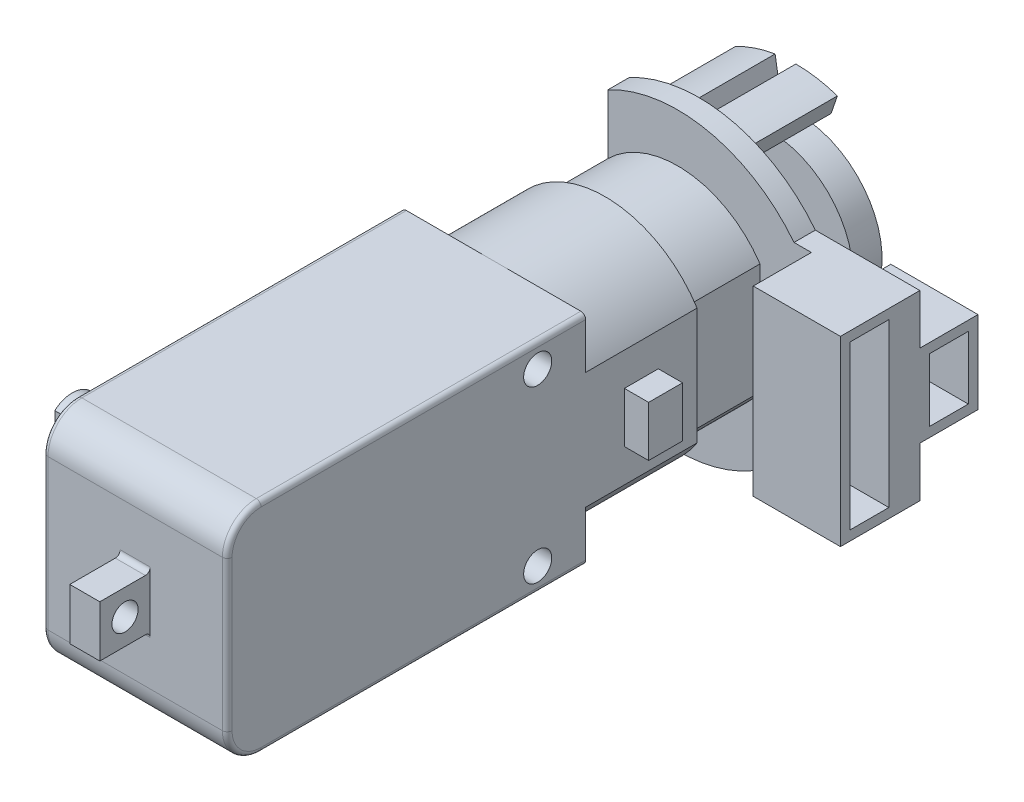
SolidWorks part; units mm, degrees
ref_plane "Front Plane" through (0, 0, 0) normal (0, 0, 1) x (1, 0, 0)
ref_plane "Top Plane" through (0, 0, 0) normal (0, 1, 0) x (1, 0, 0)
ref_plane "Right Plane" through (0, 0, 0) normal (1, 0, 0) x (0, 0, -1)
sketch "Sketch1" plane through (0, 0, 0) normal (1, 0, 0) x (0, 0, -1)
  line L0 (0, 0) -> (-38.2014, 0) construction
  line L2 (-37, -11.25) -> (0, -11.25)
  line L3 (-37, -11.25) -> (-37, 11.25)
  line L4 (-37, 11.25) -> (0, 11.25)
  line L5 (0, -11.25) -> (0, 11.25)
  line L6 (-37, -11.25) -> (0, 11.25) construction
  line L7 (-37, 11.25) -> (0, -11.25) construction
  point P3 (-18.5, 0)
  dimension "D1" = 22.5
  dimension "D2" = 37
extrude "Boss-Extrude1" add sketch "Sketch1" along normal blind 19
sketch "Sketch2" plane through (0, 0, 37) normal (0, 0, 1) x (1, 0, 0)
  line L0 (9.5, 11.25) -> (9.5, -11.25) construction
  line L1 (19, 11.25) -> (0, 11.25) construction
  line L2 (19, -11.25) -> (0, -11.25) construction
  line L3 (0, 0) -> (19, 0) construction
  line L4 (19, 11.25) -> (19, -11.25) construction
  line L6 (7.95, -2.65) -> (11.05, -2.65)
  line L7 (7.95, -2.65) -> (7.95, 2.65)
  line L8 (7.95, 2.65) -> (11.05, 2.65)
  line L9 (11.05, -2.65) -> (11.05, 2.65)
  line L10 (7.95, -2.65) -> (11.05, 2.65) construction
  line L11 (7.95, 2.65) -> (11.05, -2.65) construction
  point P11 (9.5, 0)
  dimension "D1" = 3.1
  dimension "D2" = 5.3
extrude "Boss-Extrude2" add sketch "Sketch2" along normal blind 5.2
sketch "Sketch3" plane through (11.05, 0, 0) normal (1, 0, 0) x (0, 0, -1)
  line L0 (-42.2, 2.65) -> (-37, -2.65) construction
  line L1 (-42.2, -2.65) -> (-37, 2.65) construction
  line L2 (-37, 11.25) -> (-37, -11.25) construction
  line L3 (-37, -2.65) -> (-37, 2.65) construction
  line L4 (-42.2, 2.65) -> (-37, 2.65) construction
  circle A0 centre (-39.6, 0) radius 1.35
  dimension "D1" = 2.7
extrude "Cut-Extrude1" cut sketch "Sketch3" against normal through all
fillet "Fillet1" radius 3.5 2 edges at (9.5, -11.25, 37) (9.5, 11.25, 37)
sketch "Sketch4" plane through (19, 0, 0) normal (1, 0, 0) x (0, 0, -1)
  line L0 (-25, 11.25) -> (-25, -11.25) construction
  line L1 (0, 11.25) -> (-33.5, 11.25) construction
  line L2 (-33.5, -11.25) -> (0, -11.25) construction
  line L3 (-37, 0) -> (0, 0) construction
  line L4 (-37, 7.75) -> (-37, -7.75) construction
  circle A0 centre (-25, 0) radius 3.6
  dimension "D2" = 7.2
  dimension "D1" = 12
extrude "Boss-Extrude3" add sketch "Sketch4" along normal blind 0.1
sketch "Sketch5" plane through (0, 0, 0) normal (-1, 0, 0) x (0, 0, 1)
  circle A0 centre (25, 0) radius 3.6 construction
  circle A1 centre (25, 0) radius 3.6
extrude "Boss-Extrude4" add sketch "Sketch5" along normal blind 0.1
sketch "Sketch6" plane through (19.1, 0, 0) normal (1, 0, 0) x (0, 0, -1)
  circle A0 centre (-25, 0) radius 2.7
  dimension "D1" = 5.4
extrude "Boss-Extrude5" add sketch "Sketch6" along normal blind 8.9
sketch "Sketch7" plane through (-0.1, 0, 0) normal (-1, 0, 0) x (0, 0, 1)
  circle A0 centre (25, 0) radius 2.7 construction
  circle A1 centre (25, 0) radius 2.7
extrude "Boss-Extrude6" add sketch "Sketch7" along normal blind 8.9
fillet "Fillet2" radius 0.5 2 edges at (9.5, -2.65, 37) (9.5, 2.65, 37)
sketch "Sketch8" plane through (28, 0, 0) normal (1, 0, 0) x (0, 0, -1)
  line L0 (-26.8, 2.0125) -> (-26.8, -2.0125)
  line L2 (-23.2, -2.0125) -> (-23.2, 2.0125)
  circle A0 centre (-25, 0) radius 2.7 construction
  circle A1 centre (-25, 0) radius 2.7
  circle M3 centre (-25, 0) radius 2.7
  dimension "D1" = 3.6
extrude "Cut-Extrude2" cut sketch "Sketch8" against normal blind 8.2 contours L0 M3 | L2 M3
sketch "Sketch9" plane through (-9, 0, 0) normal (-1, 0, 0) x (0, 0, 1)
  line L0 (26.8, 2.0125) -> (26.8, -2.0125) construction
  line L1 (23.2, -2.0125) -> (23.2, 2.0125) construction
  line L2 (26.8, 2.0125) -> (26.8, -2.0125)
  line L3 (23.2, -2.0125) -> (23.2, 2.0125)
  circle A0 centre (25, 0) radius 2.7 construction
  circle A1 centre (25, 0) radius 2.7
  circle M1 centre (25, 0) radius 2.7
extrude "Cut-Extrude3" cut sketch "Sketch9" against normal blind 8.2 contours L3 M1 | L2 M1
hole_wizard "M2x0.4 Tapped Hole1" positions "Sketch11" profile "Sketch10" tap size "M2x0.4" standard "ANSI Metric"
sketch "Sketch11" plane through (28, 0, 0) normal (1, 0, 0) x (0, 0, -1)
  point P0 (-25, 0)
sketch "Sketch10" plane through (28, 0, 25) normal (0, 1, 0) x (0, 0, -1)
  line L0 (0, 0) -> (0, 5.6807)
  line L1 (0, 5.6807) -> (0.8, 5.2)
  line L2 (0.8, 5.2) -> (0.8, 0)
  line L5 (0.8, 0) -> (0, 0)
  line L10 (0, 5.6807) -> (-0.8, 5.2) construction
  line L11 (0, -6.35) -> (0, 107.95) construction
  dimension "Tap Drill Dia." = 1.6
  dimension "Tap Drill Depth" = 5.2
  dimension "Drill Angle" = 118
cosmetic thread "Hole Thread1" parameters "D1"=4, "D2"=2
hole_wizard "M2x0.4 Tapped Hole2" positions "Sketch15" profile "Sketch14" tap size "M2x0.4" standard "ANSI Metric"
sketch "Sketch15" plane through (-9, 0, 0) normal (-1, 0, 0) x (0, 0, 1)
  point P0 (25, 0)
sketch "Sketch14" plane through (-9, 0, 25) normal (0, 1, 0) x (0, 0, 1)
  line L0 (0, 0) -> (0, 5.6807)
  line L1 (0, 5.6807) -> (0.8, 5.2)
  line L2 (0.8, 5.2) -> (0.8, 0)
  line L5 (0.8, 0) -> (0, 0)
  line L10 (0, 5.6807) -> (-0.8, 5.2) construction
  line L11 (0, -6.35) -> (0, 107.95) construction
  dimension "Tap Drill Dia." = 1.6
  dimension "Tap Drill Depth" = 5.2
  dimension "Drill Angle" = 118
cosmetic thread "Hole Thread2" parameters "D1"=4, "D2"=2
sketch "Sketch16" plane through (0, 0, 0) normal (-1, 0, 0) x (0, 0, 1)
  line L0 (0, 0) -> (21.4, 0) construction
  circle A0 centre (25, 0) radius 3.6 construction
  circle A1 centre (13.75, 0) radius 1.95
  circle A4 centre (25, 0) radius 3.6 construction
  dimension "D1" = 3.9
  dimension "D2" = 5.7
extrude "Boss-Extrude7" add sketch "Sketch16" along normal blind 2
sketch "Sketch17" plane through (0, 0, 0) normal (0, 0, -1) x (-1, 0, 0)
  line L0 (-19, 11.25) -> (0, -11.25) construction
  line L1 (-19, -11.25) -> (0, 11.25) construction
  line L2 (-19, -11.25) -> (-19, 11.25) construction
  line L3 (-19, -11.25) -> (-19, 11.25)
  line L6 (-1.3, -11.25) -> (-1.3, 11.25)
  line L7 (-1.3, -11.25) -> (-1.3, 11.25)
  circle A0 centre (-9.5, 0) radius 11.25
  dimension "D1" = 1.3
extrude "Boss-Extrude8" add sketch "Sketch17" along normal blind 11.5 contours L7 A0 L3
sketch "Sketch18" plane through (19, 0, 0) normal (1, 0, 0) x (0, 0, -1)
  line L0 (11.5, 0) -> (0, 0) construction
  line L1 (11.5, 6.026) -> (11.5, -6.026) construction
  line L3 (4, -2.6) -> (7.5, -2.6)
  line L4 (4, -2.6) -> (4, 2.6)
  line L5 (4, 2.6) -> (7.5, 2.6)
  line L6 (7.5, -2.6) -> (7.5, 2.6)
  line L7 (4, -2.6) -> (7.5, 2.6) construction
  line L8 (4, 2.6) -> (7.5, -2.6) construction
  point P5 (5.75, 0)
  dimension "D1" = 4
  dimension "D2" = 5.2
  dimension "D3" = 3.5
extrude "Boss-Extrude9" add sketch "Sketch18" along normal blind 2.5
sketch "Sketch19" plane through (1.3, 0, 0) normal (-1, 0, 0) x (0, 0, 1)
  line L0 (-7.5, 2.6) -> (-4, 2.6) construction
  line L1 (-4, 2.6) -> (-4, -2.6) construction
  line L2 (-4, -2.6) -> (-7.5, -2.6) construction
  line L3 (-7.5, -2.6) -> (-7.5, 2.6) construction
  line L4 (-7.5, 2.6) -> (-4, 2.6)
  line L5 (-4, 2.6) -> (-4, -2.6)
  line L6 (-4, -2.6) -> (-7.5, -2.6)
  line L7 (-7.5, -2.6) -> (-7.5, 2.6)
extrude "Boss-Extrude10" add sketch "Sketch19" along normal blind 2.5
sketch "Sketch20" plane through (0, 0, -11.5) normal (0, 0, -1) x (-1, 0, 0)
  line L20 (-18, 6.026) -> (-18, -6.026)
  line L21 (-18, 5.7282) -> (-18, -5.7282)
  line L23 (-2.3, -7.7021) -> (-2.3, 7.7021)
  line L24 (-2.3, -7.2954) -> (-2.3, 7.2954)
  arc A30 (-2.0289, 7.0175) -> (-18.1556, 5.4903) centre (-9.5, 0) ccw
  arc A31 (-2.3, 7.2954) -> (-18, 5.7282) centre (-9.5, 0) ccw
  arc A34 (-18.1556, -5.4903) -> (-2.0289, -7.0175) centre (-9.5, 0) ccw
  arc A35 (-18, -5.7282) -> (-2.3, -7.2954) centre (-9.5, 0) ccw
  dimension "D1" = 1
  dimension "D2" = 1
  dimension "D3" = 1
  dimension "D4" = 1
extrude "Boss-Extrude11" add sketch "Sketch20" along normal blind 13.5
fillet "Fillet3" radius 1.7 2 edges at (10.5181, -10.1993, -25) (10.5181, 10.1993, -25)
sketch "Sketch21" plane through (0, 0, -25) normal (0, 0, -1) x (-1, 0, 0)
  line L0 (-5.5, 3) -> (-5.5, -3)
  circle A0 centre (-9.5, 0) radius 5
  dimension "D1" = 10
  dimension "D2" = 9
extrude "Boss-Extrude12" add sketch "Sketch21" along normal blind 2 contours L0 A0
sketch "Sketch23" plane through (0, 0, -25) normal (0, 0, -1) x (-1, 0, 0)
  line L0 (-9.5, 10.25) -> (-9.5, -11.25) construction
  line L1 (-7.9, 7) -> (-7.9, -7) construction
  line L2 (-11.1, 13.5) -> (-7.9, 13.5)
  line L3 (-11.1, 13.5) -> (-11.1, 7)
  line L4 (-11.1, 7) -> (-7.9, 7)
  line L5 (-7.9, 13.5) -> (-7.9, 7)
  line L6 (-11.1, 13.5) -> (-7.9, 7) construction
  line L7 (-11.1, 7) -> (-7.9, 13.5) construction
  line L8 (-11.1, -15.5) -> (-7.9, -15.5)
  line L9 (-11.1, -15.5) -> (-11.1, -7)
  line L10 (-11.1, -7) -> (-7.9, -7)
  line L11 (-7.9, -15.5) -> (-7.9, -7)
  line L12 (-11.1, -15.5) -> (-7.9, -7) construction
  line L13 (-11.1, -7) -> (-7.9, -15.5) construction
  line L14 (-9.5, 0) -> (-7.9, 7) construction
  line L16 (-9.5, 0) -> (-7.9, -7) construction
  arc A0 (-2.3, 7.2954) -> (-18, 5.7282) centre (-9.5, 0) ccw construction
  arc A1 (-2.3, 4.6111) -> (-18, 0.9233) centre (-9.5, 0) ccw construction
  arc A2 (-2.3, 4.6111) -> (-18, 0.9233) centre (-9.5, 0) ccw construction
  dimension "D1" = 14
  dimension "D2" = 3.2
extrude "Cut-Extrude4" cut sketch "Sketch23" against normal blind 6
sketch "Sketch24" plane through (0, -11.25, 0) normal (0, -1, 0) x (1, 0, 0)
  line L0 (19, 25) -> (0, 25) construction
  line L1 (19, 33.5) -> (19, 0) construction
  line L2 (0, 33.5) -> (0, 0) construction
  line L3 (28, 25) -> (19, 25) construction
  line L4 (28, 23.2) -> (28, 26.8) construction
ref_plane "Plane1" through (0, 0, 25) normal (0, 0, 1) x (-1, 0, 0)
sketch "Sketch25" plane through (19, 0, 0) normal (1, 0, 0) x (0, 0, -1)
  line L0 (-4.95, 11.25) -> (-4.95, -11.25) construction
  line L1 (0, 11.25) -> (-33.5, 11.25) construction
  line L2 (-33.5, -11.25) -> (0, -11.25) construction
  line L4 (0, 6.026) -> (0, 11.25) construction
  line L5 (-37, 7.75) -> (-37, -7.75) construction
  circle A0 centre (-4.95, 8.8) radius 1.45
  circle A1 centre (-4.95, -8.8) radius 1.45
  dimension "D1" = 2.9
  dimension "D2" = 14.7
  dimension "D5" = 3.5
  dimension "D3" = 1
  dimension "D4" = 1
  dimension "D6" = 30.6
extrude "Cut-Extrude5" cut sketch "Sketch25" against normal through all
fillet "Fillet4" radius 0.5 10 edges at (0, -11.25, 16.75) (0, -10.2249, 35.9749) (0, 0, 37) (0, 10.2249, 35.9749) (19, -11.25, 16.75) (19, -10.2249, 35.9749) (19, 0, 37) (19, 10.2249, 35.9749) (0, 11.25, 16.75) (19, 11.25, 16.75)
sketch "Sketch26" plane through (0, 0, -27) normal (0, 0, -1) x (-1, 0, 0)
  circle A0 centre (-9.5, 0) radius 1
  dimension "D1" = 2
extrude "Boss-Extrude13" add sketch "Sketch26" along normal blind 4.5
sketch "Sketch27" plane through (0, 0, 0) normal (-1, 0, 0) x (0, 0, 1)
  line L0 (25, 0) -> (16.1055, -5.3723) construction
sketch "Sketch28" plane through (0, 0, -31.5) normal (0, 0, -1) x (-1, 0, 0)
  circle A0 centre (-9.5, 0) radius 8.6
  dimension "D1" = 17.2
extrude "Boss-Extrude14" add sketch "Sketch28" against normal blind 3
sketch "Sketch29" plane through (0, 0, -19) normal (0, 0, -1) x (-1, 0, 0)
  line L0 (-18, 5.7282) -> (-18, -5.7282) construction
  line L1 (-18, 5.7282) -> (-18, -5.7282)
  line L2 (-2.3, 7.2954) -> (-2.3, 13.4433)
  line L3 (-9.5, 0) -> (-39.9184, 0) construction
  line L4 (-23, 7.0931) -> (-23, -7.0931)
  line L5 (-2.3, 7.2954) -> (10.3813, 16.3683) construction
  line L6 (-2.3, -7.2954) -> (-2.3, -13.4433)
  line L7 (-7.9, -8.399) -> (-7.9, -10.1244) construction
  line L8 (-2.3, 13.4433) -> (7.472, 20.4347) construction
  line L9 (-32.3, -9.4) -> (-21.5084, -9.4)
  line L10 (-32.3, -9.4) -> (-32.3, 9.4)
  line L11 (-32.3, 9.4) -> (-21.5084, 9.4)
  line L12 (-21.5084, -9.4) -> (-21.5084, 9.4)
  line L13 (-32.3, -9.4) -> (-21.5084, 9.4) construction
  line L14 (-32.3, 9.4) -> (-21.5084, -9.4) construction
  line L15 (-11.1, -10.1244) -> (-11.1, -8.399) construction
  line L16 (-7.9, -8.399) -> (-7.9, -10.1244)
  line L17 (-11.1, -10.1244) -> (-11.1, -8.399)
  line L18 (-7.9, 10.1244) -> (-7.9, 8.399) construction
  line L19 (-11.1, 8.399) -> (-11.1, 10.1244) construction
  line L20 (-7.9, 10.1244) -> (-7.9, 8.399)
  line L21 (-11.1, 8.399) -> (-11.1, 10.1244)
  arc A0 (-2.3, 7.2954) -> (-18, 5.7282) centre (-9.5, 0) ccw construction
  arc A1 (-2.3, 7.2954) -> (-7.9, 10.1244) centre (-9.5, 0) ccw
  arc A2 (-18, -5.7282) -> (-2.3, -7.2954) centre (-9.5, 0) ccw construction
  arc A3 (-18, -5.7282) -> (-11.1, -10.1244) centre (-9.5, 0) ccw
  arc A4 (-2.3, 13.4433) -> (-23, 7.0931) centre (-9.5, 0) ccw
  arc A5 (-23, -7.0931) -> (-2.3, -13.4433) centre (-9.5, 0) ccw
  arc A6 (-23, -7.0931) -> (1.2122, -10.8541) centre (-9.5, 0) ccw construction
  arc A9 (-7.9, -10.1244) -> (-2.3, -7.2954) centre (-9.5, 0) ccw
  arc A10 (-18, -5.7282) -> (-2.3, -7.2954) centre (-9.5, 0) ccw construction
  arc A11 (-11.1, 10.1244) -> (-18, 5.7282) centre (-9.5, 0) ccw
  arc A12 (-2.3, 7.2954) -> (-18, 5.7282) centre (-9.5, 0) ccw construction
  arc A13 (-11.1, -10.1244) -> (-7.9, -10.1244) centre (-9.5, 0) ccw construction
  arc A14 (-11.1, -10.1244) -> (-7.9, -10.1244) centre (-9.5, 0) ccw
  arc A15 (-7.9, 10.1244) -> (-11.1, 10.1244) centre (-9.5, 0) ccw construction
  arc A16 (-7.9, 10.1244) -> (-11.1, 10.1244) centre (-9.5, 0) ccw
  arc A17 (-11.1, 9.2617) -> (-7.9, 9.2617) centre (-9.5, 11.7994) ccw
  arc A18 (-11.1, -9.2617) -> (-7.9, -9.2617) centre (-9.5, -11.7994) cw
  point P21 (-26.9042, 0)
  arc M18 (-7.9, 10.1244) -> (-11.1, 10.1244) centre (-9.5, 0) ccw
  line M19 (-11.1, 10.1244) -> (-11.1, 7)
  dimension "D1" = 3
  dimension "D5" = 3
  dimension "D3" = 18.8
  dimension "D4" = 30
  dimension "D2" = 5
extrude "Boss-Extrude20" add sketch "Sketch29" along normal blind 2.2 contours A14 A3 L1 A11 A1 L2 A4 L12 A5 L6 A9 M18 | A18 L17 A14 L16 | A17 L20 M19 M18 | A5 L4 A4 L11 L10 L9 | L4 A5 L12 A4
sketch "Sketch30" plane through (0, 0, -19) normal (0, 0, 1) x (1, 0, 0)
  line L0 (32.3, -9.4) -> (21.5084, -9.4) construction
  line L1 (32.3, 9.4) -> (23.3, 9.4)
  line L2 (32.3, 9.4) -> (32.3, -9.4)
  line L3 (32.3, -9.4) -> (23.3, -9.4)
  line L4 (23.3, 9.4) -> (23.3, -9.4)
  dimension "D1" = 9
extrude "Boss-Extrude21" add sketch "Sketch30" along normal blind 6
sketch "Sketch31" plane through (0, 0, -21.2) normal (0, 0, -1) x (-1, 0, 0)
  line L0 (-32.3, -9.4) -> (-32.3, 9.4) construction
  line L1 (-32.3, 4.25) -> (-23.3, 4.25)
  line L2 (-32.3, 4.25) -> (-32.3, -4.25)
  line L3 (-32.3, -4.25) -> (-23.3, -4.25)
  line L4 (-23.3, 4.25) -> (-23.3, -4.25)
  line L5 (-23.3, 0) -> (-9.5, 0) construction
  dimension "D1" = 9
  dimension "D2" = 8.5
extrude "Boss-Extrude22" add sketch "Sketch31" along normal blind 6
sketch "Sketch32" plane through (32.3, 0, 0) normal (1, 0, 0) x (0, 0, -1)
  line L8 (18, 8.4) -> (18, -8.4)
  line L9 (22.2, 3.25) -> (22.2, -3.25)
  line L10 (19, 15.25) -> (19, 9.4) construction
  line L11 (21.2, 5.7282) -> (21.2, 10.1244) construction
  line L16 (20.2, 8.4) -> (14, 8.4)
  line L17 (14, 8.4) -> (14, -8.4)
  line L18 (14, -8.4) -> (20.2, -8.4)
  line L19 (20.2, -8.4) -> (20.2, -3.25)
  line L20 (20.2, -3.25) -> (26.2, -3.25)
  line L21 (26.2, -3.25) -> (26.2, 3.25)
  line L22 (26.2, 3.25) -> (20.2, 3.25)
  line L23 (20.2, 3.25) -> (20.2, 8.4)
  line L24 (20.2, 8.4) -> (14, 8.4)
  line L25 (14, 8.4) -> (14, -8.4)
  line L26 (14, -8.4) -> (20.2, -8.4)
  line L27 (20.2, -8.4) -> (20.2, -3.25)
  line L28 (20.2, -3.25) -> (26.2, -3.25)
  line L29 (26.2, -3.25) -> (26.2, 3.25)
  line L30 (26.2, 3.25) -> (20.2, 3.25)
  line L31 (20.2, 3.25) -> (20.2, 8.4)
  dimension "D2" = 1
  dimension "D3" = 1
  dimension "D1" = 1
extrude "Cut-Extrude6" cut sketch "Sketch32" against normal blind 6 contours L25 L26 L8 L24 | L29 L30 L9 L28
sketch "Sketch33" plane through (0, 0, -21.2) normal (0, 0, -1) x (-1, 0, 0)
  line L0 (-7.035, 15.0495) -> (-7.035, -15.0495) construction
  line L1 (-2.3, 13.4433) -> (-9.5, 0)
  line L2 (-9.5, 0) -> (-2.3, -13.4433)
  line L3 (-9.5, 0) -> (-7.035, 15.0495)
  line L4 (-9.5, 0) -> (-7.035, -15.0495)
  line L5 (-9.5, 0) -> (-9.5, 15.25)
  line L6 (-9.5, 0) -> (-9.5, -15.25)
  line L7 (-9.5, 0) -> (-14.4324, 14.4303)
  line L8 (-9.5, 0) -> (-14.4324, -14.4303)
  line L9 (-14.4324, 14.4303) -> (-14.4324, -14.4303) construction
  circle A0 centre (-9.5, 0) radius 11.25
  circle A1 centre (-9.5, 0) radius 13.25
  arc A2 (-2.3, 7.2954) -> (-7.9, 10.1244) centre (-9.5, 0) ccw construction
  arc A3 (-2.3, 13.4433) -> (-21.5084, 9.4) centre (-9.5, 0) ccw construction
  arc A4 (-21.5084, -9.4) -> (-2.3, -13.4433) centre (-9.5, 0) ccw construction
  dimension "D1" = 1
  dimension "D2" = 2
  dimension "D3" = 5
  dimension "D4" = 5
extrude "Boss-Extrude23" add sketch "Sketch33" along normal blind 10 contours L5 A1 L7 A0 | L1 A1 L3 A0 | L8 A1 L6 A0 | L4 A1 L2 A0
sketch "Sketch34" plane through (19, 0, 0) normal (1, 0, 0) x (0, 0, -1)
  circle A0 centre (-25, 0) radius 7.4972
extrude "Cut-Extrude7" cut sketch "Sketch34" along normal blind 33
